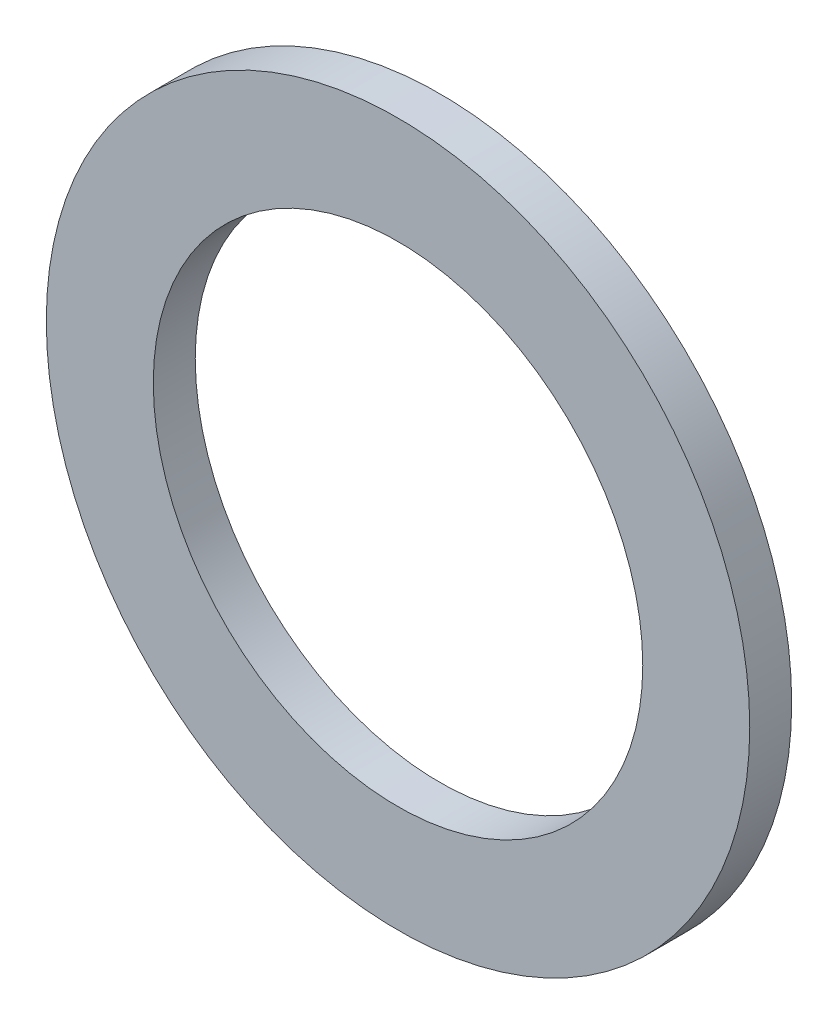
SolidWorks part; units mm, degrees
material "Acrylic (Medium-high impact)"
ref_plane "Front Plane" through (0, 0, 0) normal (0, 0, 1) x (1, 0, 0)
ref_plane "Top Plane" through (0, 0, 0) normal (0, 1, 0) x (1, 0, 0)
ref_plane "Right Plane" through (0, 0, 0) normal (1, 0, 0) x (0, 0, -1)
sketch "Sketch2" plane through (0, 0, 0) normal (0, 0, 1) x (1, 0, 0)
  circle A0 centre (0, 0) radius 25.15
  dimension "D1" = 50.3
extrude "Boss-Extrude1" add sketch "Sketch2" along normal blind 3
sketch "Sketch3" plane through (0, 0, 0) normal (0, 0, -1) x (-1, 0, 0)
  circle A0 centre (0, 0) radius 17.5
  dimension "D1" = 35
extrude "Cut-Extrude1" cut sketch "Sketch3" against normal blind 3 contours A0
